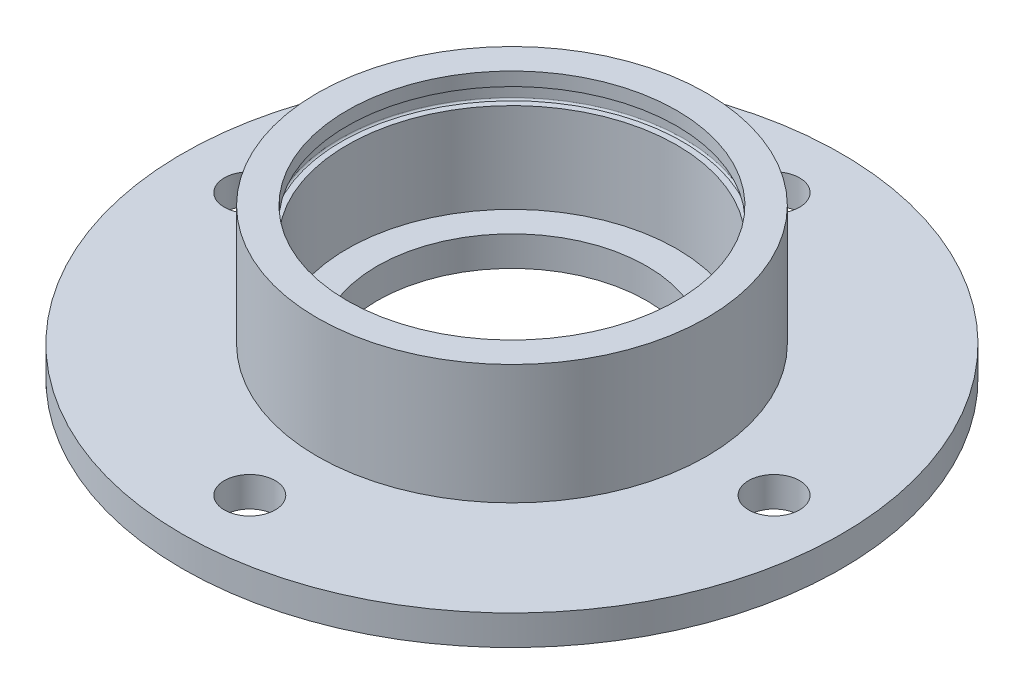
SolidWorks part; units mm, degrees
ref_plane "Front" through (0, 0, 0) normal (0, 0, 1) x (1, 0, 0)
ref_plane "Top" through (0, 0, 0) normal (0, 1, 0) x (1, 0, 0)
ref_plane "Right" through (0, 0, 0) normal (1, 0, 0) x (0, 0, -1)
sketch "Sketch1" plane through (0, 0, 0) normal (0, 0, 1) x (1, 0, 0)
  line L0 (0, 17.954) -> (0, -17.7415) construction
  line L1 (9, 0) -> (11, 0)
  line L2 (11, 0) -> (11, 8)
  line L3 (11, 8) -> (13, 8)
  line L4 (13, 8) -> (13, 0)
  line L5 (13, 0) -> (22, 0)
  line L6 (22, 0) -> (22, -2)
  line L7 (22, -2) -> (9, -2)
  line L8 (9, -2) -> (9, 0)
  dimension "D1" = 9
  dimension "D2" = 11
  dimension "D3" = 2
  dimension "D4" = 9
  dimension "D5" = 2
  dimension "D6" = 8
revolve "Revolve1" add sketch "Sketch1" angle 360 about L0
sketch "Sketch2" [suppressed] plane through (0, 0, 0) normal (0, 1, 0) x (1, 0, 0)
  circle A0 centre (0, 0) radius 11
extrude "Cut-Extrude1" [suppressed] cut sketch "Sketch2" against normal through all
ref_plane "Plane1" through (0, 17.954, 0) normal (-1, 0, 0) x (0, 0, 1)
sketch "Sketch4" plane through (0, 17.954, 0) normal (-1, 0, 0) x (0, 0, 1)
  line L0 (11.39, -11.954) -> (9.9, -11.954)
  line L1 (9.9, -11.954) -> (9.9, -10.854)
  line L2 (9.9, -10.854) -> (11.39, -10.854)
  line L3 (11.5, -10.964) -> (11.5, -11.844)
  line L4 (0, -50) -> (0, 50) construction
  line L5 (11, -17.954) -> (-11, -17.954) construction
  arc A0 (11.5, -11.844) -> (11.39, -11.954) centre (11.39, -11.844) cw
  arc A1 (11.5, -10.964) -> (11.39, -10.854) centre (11.39, -10.964) ccw
  dimension "D1" = 0.11
  dimension "D2" = 0.11
  dimension "D3" = 6
revolve "Groove for BS 3673 P4 - B022M, Internal Circlip1" cut sketch "Sketch4"
hole_wizard "M3 Clearance Hole1" positions "Sketch5" profile "Sketch6" hole size "M3" standard "ISO" end condition through all
sketch "Sketch5" plane through (0, 0, 0) normal (0, 1, 0) x (1, 0, 0)
  circle A0 centre (0, 0) radius 17.5 construction
  circle A1 centre (0, 0) radius 22 construction
  point P0 (0, 17.5)
  point P7 (17.5, 0)
  point P9 (0, -17.5)
  point P11 (-17.5, 0)
  point P14 (17.0454, 0)
  point P15 (16.724, 0)
  dimension "D1" = 4.5
  dimension "D2" = 35
sketch "Sketch6" plane through (0, 0, -17.5) normal (1, 0, 0) x (0, 0, 1)
  line L0 (0, 0) -> (0, 2)
  line L1 (0, 2) -> (1.7, 2)
  line L2 (1.7, 2) -> (1.7, 0)
  line L5 (1.7, 0) -> (0, 0)
  line L11 (0, -6.35) -> (0, 107.95) construction
  dimension "Thru Hole Dia." = 3.4
  dimension "Thru Hole Depth" = 2
